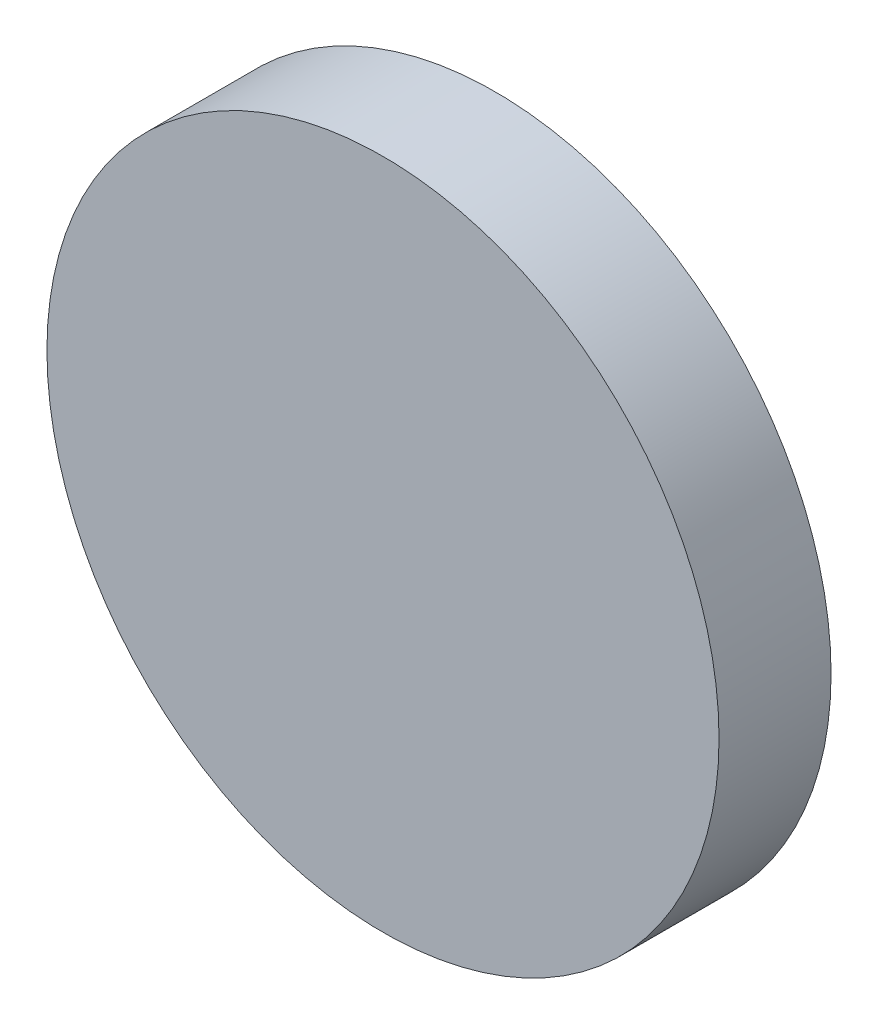
SolidWorks part; units mm, degrees
ref_plane "Alzado" through (0, 0, 0) normal (0, 0, 1) x (1, 0, 0)
ref_plane "Planta" through (0, 0, 0) normal (0, 1, 0) x (1, 0, 0)
ref_plane "Vista lateral" through (0, 0, 0) normal (1, 0, 0) x (0, 0, -1)
sketch "Croquis1" plane through (0, 0, 0) normal (0, 0, 1) x (1, 0, 0)
  circle A0 centre (0, 0) radius 6
extrude "Saliente-Extruir1" add sketch "Croquis1" along normal blind 2
